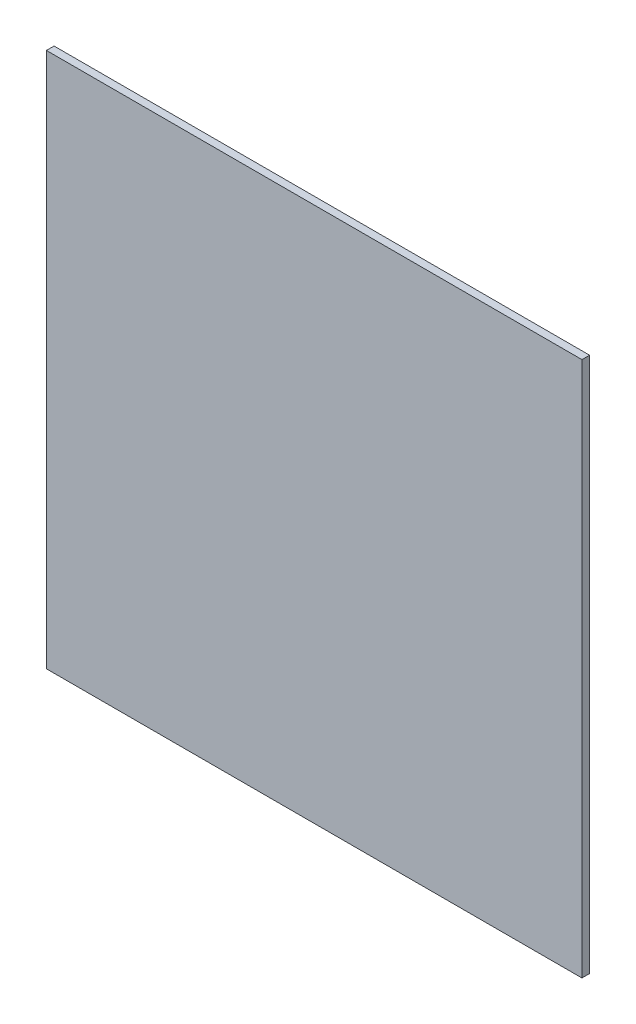
SolidWorks part; units mm, degrees
ref_plane "前视基准面" through (0, 0, 0) normal (0, 0, 1) x (1, 0, 0)
ref_plane "上视基准面" through (0, 0, 0) normal (0, 1, 0) x (1, 0, 0)
ref_plane "右视基准面" through (0, 0, 0) normal (1, 0, 0) x (0, 0, -1)
sketch "草图1" plane through (0, 0, 0) normal (0, 0, 1) x (1, 0, 0)
  line L0 (-49.8973, -319.1589) -> (650.1027, -319.1589) construction
  line L1 (-49.8973, 30.8411) -> (650.1027, 30.8411)
  line L2 (-49.8973, 30.8411) -> (-49.8973, -669.1589)
  line L3 (-49.8973, -669.1589) -> (650.1027, -669.1589)
  line L4 (650.1027, 30.8411) -> (650.1027, -669.1589)
  dimension "D1" = 700
extrude "凸台-拉伸1" add sketch "草图1" along normal blind 10
